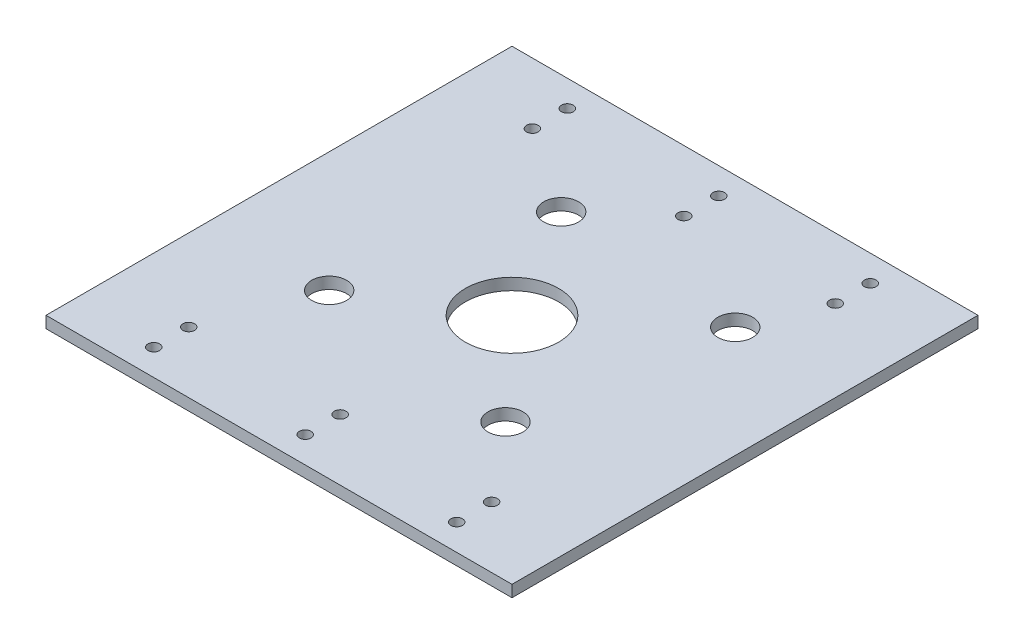
SolidWorks part; units mm, degrees
ref_plane "Front Plane" through (0, 0, 0) normal (0, 0, 1) x (1, 0, 0)
ref_plane "Top Plane" through (0, 0, 0) normal (0, 1, 0) x (1, 0, 0)
ref_plane "Right Plane" through (0, 0, 0) normal (1, 0, 0) x (0, 0, -1)
sketch "Sketch2" plane through (0, 0, 0) normal (0, 1, 0) x (1, 0, 0)
  line L1 (-100, -100) -> (100, -100)
  line L2 (-100, -100) -> (-100, 100)
  line L3 (-100, 100) -> (100, 100)
  line L4 (100, -100) -> (100, 100)
  line L5 (-100, -100) -> (100, 100) construction
  line L6 (-100, 100) -> (100, -100) construction
  point P0 (0, 0)
  dimension "D1" = 200
  dimension "D2" = 200
extrude "Boss-Extrude1" add sketch "Sketch2" along normal blind 5
sketch "Sketch3" plane through (0, 5, 0) normal (0, 1, 0) x (1, 0, 0)
  line L0 (100, 100) -> (-100, 100) construction
  line L1 (-85, 96.25) -> (-80, 96.25)
  line L2 (-85, 96.25) -> (-85, 66.25)
  line L3 (-85, 66.25) -> (-80, 66.25)
  line L4 (-80, 96.25) -> (-80, 66.25)
  line L5 (-85, 96.25) -> (-80, 66.25) construction
  line L6 (-85, 66.25) -> (-80, 96.25) construction
  line L7 (-50, 96.25) -> (-45, 96.25)
  line L8 (-50, 96.25) -> (-50, 66.25)
  line L9 (-50, 66.25) -> (-45, 66.25)
  line L10 (-45, 96.25) -> (-45, 66.25)
  line L11 (-50, 96.25) -> (-45, 66.25) construction
  line L12 (-50, 66.25) -> (-45, 96.25) construction
  line L15 (-100, 100) -> (-100, -100) construction
  point P0 (-82.5, 81.25)
  point P5 (-47.5, 81.25)
  dimension "D1" = 5
  dimension "D2" = 30
  dimension "D3" = 30
  dimension "D4" = 3.75
  dimension "D5" = 15
extrude "Boss-Extrude2" add sketch "Sketch3" along normal blind 60
sketch "Sketch4" plane through (-45, 0, 0) normal (1, 0, 0) x (0, 0, -1)
  line L0 (66.25, 65) -> (96.25, 65) construction
  line L1 (96.25, 65) -> (96.25, 5) construction
  circle A0 centre (81.25, 55) radius 5
  dimension "D1" = 10
  dimension "D2" = 10
  dimension "D3" = 15
extrude "Cut-Extrude1" cut sketch "Sketch4" against normal up to surface (40 mm away) up to face at (-85, 35, -81.25)
fillet "Fillet1" radius 10 4 edges at (-82.5, 65, -96.25) (-82.5, 65, -66.25) (-47.5, 65, -66.25) (-47.5, 65, -96.25)
pattern_linear "LPattern1" count 3 spacing 57.5 along (1, 0, 0) count 2 spacing 136.25 along (0, 0, 1) of "Boss-Extrude2", "Cut-Extrude1", "Fillet1"
fillet "Fillet2" [suppressed] radius 30
sketch "Sketch6" plane through (0, 5, 0) normal (0, 1, 0) x (1, 0, 0)
  circle A0 centre (0, 0) radius 20
  dimension "D1" = 40
extrude "Cut-Extrude3" cut sketch "Sketch6" against normal through all
sketch "Sketch10" plane through (0, 5, 0) normal (0, 1, 0) x (1, 0, 0)
  line L0 (-65, 88.75) -> (-65, 73.75) construction
  line L1 (-80, 88.75) -> (-50, 88.75) construction
  line L2 (-50, 96.25) -> (-50, 86.25) construction
  line L3 (-80, 66.25) -> (-80, 96.25) construction
  line L4 (-65, 81.25) -> (-85, 81.25) construction
  line L5 (-85, 86.25) -> (-85, 76.25) construction
  circle A0 centre (-65, 88.75) radius 2.5
  circle A1 centre (-65, 73.75) radius 2.5
  point P9 (-65, 88.75)
  dimension "D1" = 15
  dimension "D2" = 5
extrude "Cut-Extrude4" cut sketch "Sketch10" against normal through all contours A0
pattern_linear "LPattern2" count 3 spacing 65 along (1, 0, 0) count 2 spacing 162.5 along (0, 0, 1) of "Cut-Extrude4"
sketch "Sketch11" plane through (0, 5, 0) normal (0, 1, 0) x (1, 0, 0)
  line L4 (-100, 100) -> (-100, -100)
  line L5 (-100, -100) -> (100, -100)
  line L6 (100, -100) -> (100, 100)
  line L7 (100, 100) -> (-100, 100)
  line L8 (-100, 100) -> (-100, -100)
  line L9 (-100, -100) -> (100, -100)
  line L10 (100, -100) -> (100, 100)
  line L11 (100, 100) -> (-100, 100)
  dimension "D1" = 0
extrude "Cut-Extrude5" cut sketch "Sketch11" along normal through all
sketch "Sketch12" plane through (0, 5, 0) normal (0, 1, 0) x (1, 0, 0)
  circle A0 centre (-27.8898, 49.002) radius 7.5
  circle A1 centre (-48.5007, -29.9614) radius 7.5
  circle A2 centre (38.2326, -41.0201) radius 7.5
  circle A3 centre (52.3821, 43.4338) radius 7.5
  dimension "D1" = 15
extrude "Cut-Extrude6" cut sketch "Sketch12" against normal through all
